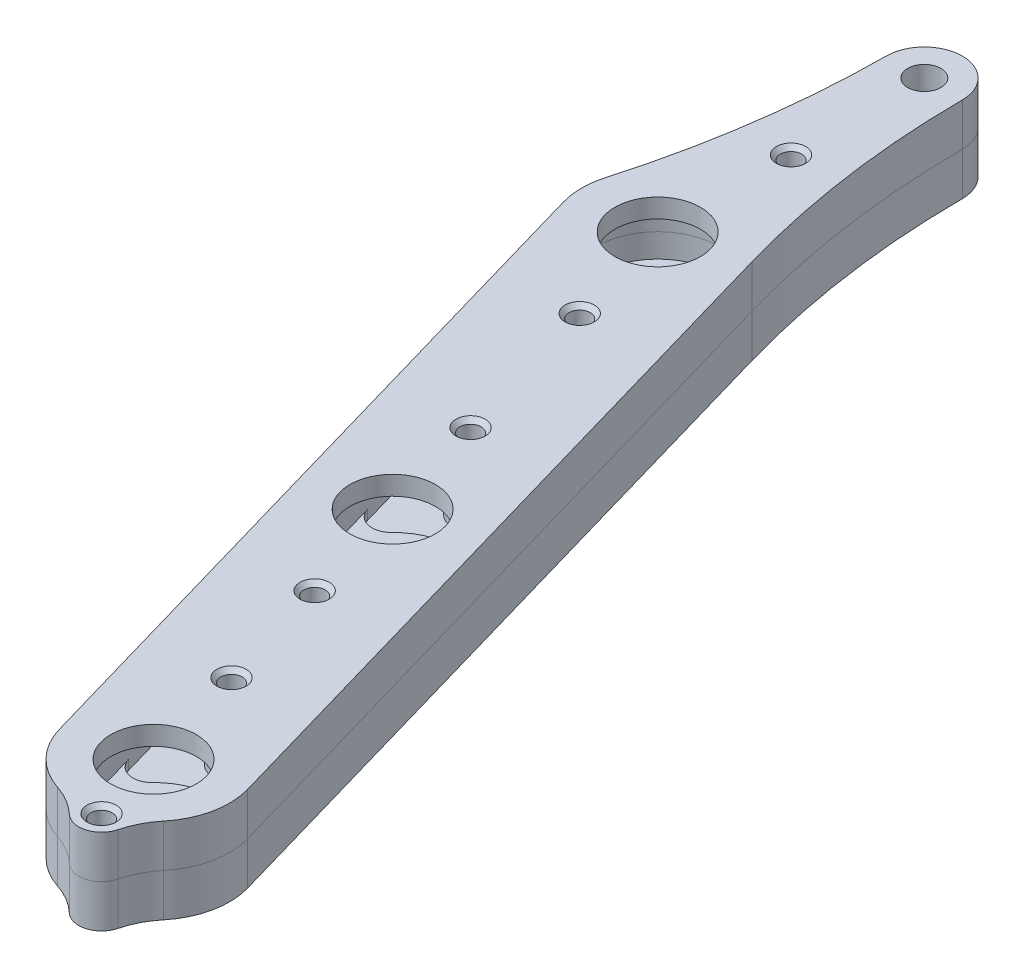
SolidWorks part; units mm, degrees
material "PE High Density"
ref_plane "Front Plane" through (0, 0, 0) normal (0, 0, 1) x (1, 0, 0)
ref_plane "Top Plane" through (0, 0, 0) normal (0, 1, 0) x (1, 0, 0)
ref_plane "Right Plane" through (0, 0, 0) normal (1, 0, 0) x (0, 0, -1)
sketch "Sketch2" plane through (0, 0, 0) normal (0, 1, 0) x (1, 0, 0)
  line L0 (43.9352, -243.758) -> (92.7419, -229.6676) construction
  line L1 (0, 0) -> (68.3386, -236.7128) construction
  line L2 (43.9352, -243.758) -> (-24.4034, -7.0452)
  line L4 (0, 0) -> (0, 89.0588) construction
  line L6 (92.7419, -229.6676) -> (24.4034, 7.0452)
  circle A0 centre (0, 0) radius 14.2875
  circle A1 centre (68.3386, -236.7128) radius 14.2875
  circle A5 centre (68.3386, -236.7128) radius 50.8 construction
  circle A6 centre (35.9306, -124.4572) radius 50.8 construction
  circle A7 centre (0, 89.0588) radius 5.5562
  arc A8 (12.7, 89.0884) -> (-12.6998, 89.1248) centre (0, 89.0588) ccw
  arc A10 (-12.6998, 89.1248) -> (-24.4227, 6.9778) centre (-317.4957, 90.7112) cw
  arc A11 (-24.4227, 6.9778) -> (-24.4034, -7.0452) centre (0, 0) ccw
  circle A13 centre (35.9306, -124.4572) radius 14.2875
  arc A14 (43.9352, -243.758) -> (60.4668, -260.8622) centre (68.3386, -236.7128) ccw
  circle A15 centre (0, 0) radius 25.4 construction
  arc A16 (12.7, 89.0884) -> (24.4034, 7.0452) centre (310.9948, 89.7837) ccw
  arc A17 (70.1248, -266.6305) -> (82.7725, -262.9792) centre (75.3838, -261.1162) ccw
  arc A18 (87.8701, -252.9509) -> (92.7419, -229.6676) centre (68.3386, -236.7128) ccw
  arc A19 (82.7725, -262.9792) -> (87.8701, -252.9509) centre (107.4017, -269.1891) cw
  arc A20 (70.1248, -266.6305) -> (60.4668, -260.8622) centre (52.5951, -285.0117) ccw
  point P1 (50.021, -173.264)
  point P2 (54.2481, -187.906)
  point P3 (54.2481, -187.906)
  point P4 (0, 0)
  point P9 (0, 0)
  point P34 (68.3386, -236.7128)
  point P38 (82.3049, -257.9284)
  dimension "D2" = 28.575
  dimension "D4" = 101.6
  dimension "D6" = 11.1125
  dimension "D8" = 25.4
  dimension "D9" = 304.8
  dimension "D11" = 25.4
  dimension "D3" = 50.8
  dimension "D10" = 15.24
  dimension "D5" = 129.54
  dimension "D7" = 89.0588
  dimension "D12" = 163.897
  dimension "D13" = 116.84
  dimension "D14" = 25.4
extrude "Boss-Extrude1" add sketch "Sketch2" along normal mid plane 28.575
sketch "Sketch3" plane through (0, 0, 0) normal (0, 1, 0) x (1, 0, 0)
  line L0 (40.3976, -162.8236) -> (51.6699, -201.869)
  line L1 (52.5992, -159.301) -> (63.8716, -198.3464)
  line L10 (-19.5227, -5.6362) -> (48.8159, -242.349)
  line L11 (0, 0) -> (68.3386, -236.7128) construction
  line L12 (4.467, -38.3664) -> (19.2619, -89.6135)
  line L17 (16.6687, -34.8438) -> (31.4636, -86.0909)
  line L18 (-19.5227, -5.6362) -> (48.8159, -242.349)
  line L20 (87.8613, -231.0766) -> (19.5227, 5.6362)
  line L21 (87.8613, -231.0766) -> (19.5227, 5.6362)
  arc A0 (52.5992, -159.301) -> (40.3976, -162.8236) centre (46.4984, -161.0623) ccw
  arc A1 (51.6699, -201.869) -> (63.8716, -198.3464) centre (57.7707, -200.1077) ccw
  circle A2 centre (68.3386, -236.7128) radius 14.2875 construction
  arc A7 (48.8159, -242.349) -> (87.8613, -231.0766) centre (68.3386, -236.7128) ccw
  arc A9 (-19.5382, 5.5822) -> (-19.5227, -5.6362) centre (0, 0) ccw
  arc A10 (-19.5382, 5.5822) -> (-19.5227, -5.6362) centre (0, 0) ccw
  arc A22 (-19.5382, 5.5822) -> (19.5227, 5.6362) centre (0, 0) cw
  arc A23 (16.6687, -34.8438) -> (4.467, -38.3664) centre (10.5678, -36.6051) ccw
  arc A24 (19.2619, -89.6135) -> (31.4636, -86.0909) centre (25.3628, -87.8522) ccw
  circle A30 centre (35.9306, -124.4572) radius 14.2875 construction
  dimension "D2" = 12.7
  dimension "D4" = 38.1
  dimension "D5" = 12.7
  dimension "D3" = 38.1
  dimension "D6" = 38.1
  dimension "D7" = 38.1
  dimension "D1" = 5.08
  dimension "D8" = 5.08
extrude "Cut-Extrude1" cut sketch "Sketch3" along normal offset from surface 3.175 and the other way offset from surface (11.1125 mm away) 3.175 up to face at (0, 14.2875, -83.5025) other way up to face at (37.6403, -14.2875, 120.4801)
sketch "Sketch4" plane through (0, 14.2875, 0) normal (0, 1, 0) x (1, 0, 0)
  circle A0 centre (35.9306, -124.4572) radius 14.2875 construction
  circle A1 centre (35.9306, -124.4572) radius 14.2875
  circle A2 centre (68.3386, -236.7128) radius 14.2875 construction
  circle A3 centre (0, 0) radius 14.2875 construction
  circle A4 centre (68.3386, -236.7128) radius 14.2875
  circle A5 centre (0, 0) radius 14.2875
extrude "Extrude-Thin1" add sketch "Sketch4" against normal blind 6.35 thin
fillet "Fillet1" radius 6.35 8 edges at (57.7243, 9.525, 126.6874) (53.1823, 9.525, 110.9548) (21.7937, 9.525, 2.2301) (85.5903, 9.525, 223.2103) (46.5449, 9.525, 234.4827) (14.1369, 9.525, 122.2271) (18.6789, 9.525, 137.9597) (-17.2517, 9.525, 13.5025)
mirror "Mirror1" about plane through (0, 0, 0) normal (0, 1, 0) of "Fillet1", "Extrude-Thin1"
sketch "Sketch5" plane through (0, -14.2875, 0) normal (0, -1, 0) x (1, 0, 0)
  line L0 (0, 0) -> (0, -89.0588) construction
  point P0 (57.7707, 200.1077)
  point P1 (46.4984, 161.0623)
  point P4 (0, -44.5294)
  point P5 (75.3838, 261.1162)
  point P8 (25.3628, 87.8522)
  point P9 (10.5678, 36.6051)
hole_wizard "CSK for #10 Flat Head Machine Screw (100)1" positions "Sketch6" profile "Sketch7" countersink size "#10" standard "ANSI Inch" end condition through all
sketch "Sketch6" plane through (0, -14.2875, 0) normal (0, -1, 0) x (-1, 0, 0)
  point P0 (-46.4984, -161.0623)
  point P3 (-57.7707, -200.1077)
  point P6 (-75.3838, -261.1162)
  point P9 (-10.5678, -36.6051)
  point P12 (-25.3628, -87.8522)
  point P15 (0, 44.5294)
sketch "Sketch7" plane through (46.4984, -14.2875, 161.0623) normal (1, 0, 0) x (0, 0, -1)
  line L0 (0, 0) -> (0, 28.575)
  line L1 (0, 28.575) -> (4.8895, 28.575)
  line L2 (2.8067, 26.179) -> (2.8067, 2.396)
  line L3 (2.8067, 2.396) -> (4.8895, 0)
  line L5 (4.8895, 0) -> (0, 0)
  line L6 (-2.8067, 2.396) -> (-4.8895, 0) construction
  line L7 (4.8895, 28.575) -> (2.8067, 26.179)
  line L8 (-4.8895, 28.575) -> (-2.8067, 26.179) construction
  line L11 (0, -6.35) -> (0, 107.95) construction
  dimension "Thru Hole Dia." = 5.6134
  dimension "Thru Hole Depth" = 28.575
  dimension "Near C'Sink Dia." = 9.779
  dimension "Near C'Sink Angle" = 82
  dimension "Far C'Sink Dia." = 9.779
  dimension "Far C'Sink Angle" = 82
sketch "Sketch8" plane through (0, 0, 0) normal (0, 1, 0) x (1, 0, 0)
  circle A0 centre (57.7707, -200.1077) radius 3.556
  circle A1 centre (46.4984, -161.0623) radius 3.556
  circle A2 centre (0, 44.5294) radius 3.556
  circle A3 centre (10.5678, -36.6051) radius 3.556
  circle A4 centre (25.3628, -87.8522) radius 3.556
  circle A5 centre (75.3838, -261.1162) radius 3.556
  dimension "D1" = 7.112
extrude "Cut-Extrude2" cut sketch "Sketch8" against normal mid plane 26.67
ref_plane "Plane1" through (0, -1.5875, 0) normal (0, -1, 0) x (-1, 0, 0)
ref_plane "Plane2" through (0, 1.5875, 0) normal (0, 1, 0) x (1, 0, 0)
split "Split2" trim tools "Top Plane" bodies to split 106 resulting bodies 112 113
